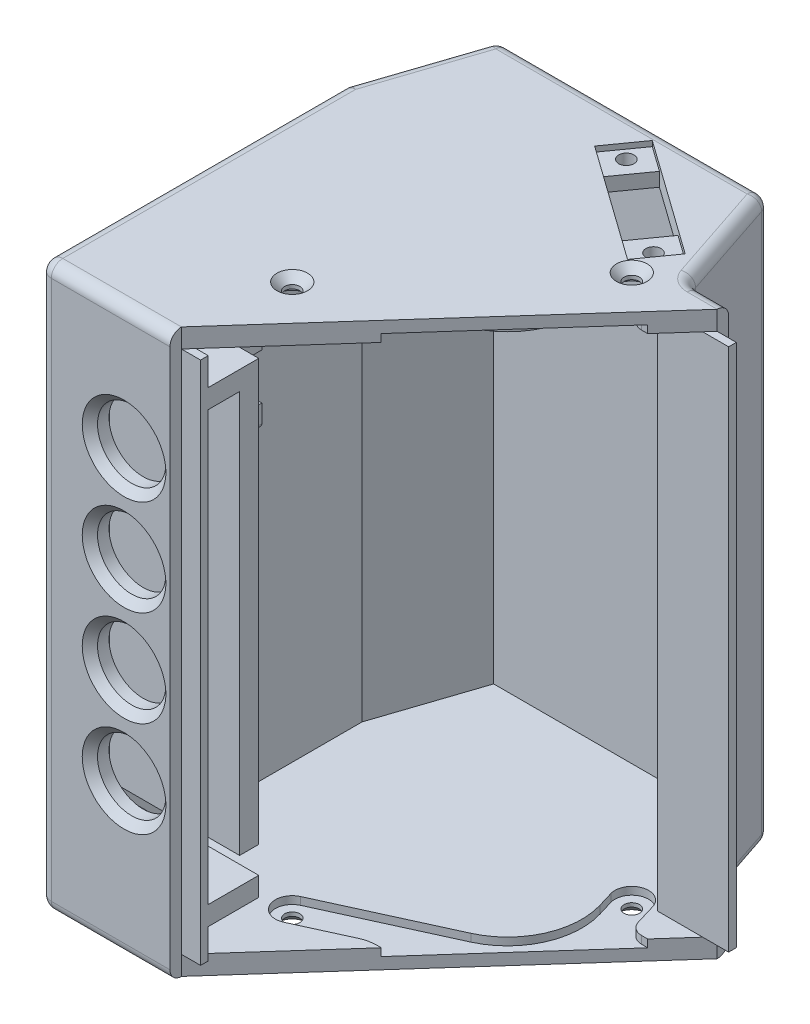
SolidWorks part; units mm, degrees
ref_plane "Plan de face" through (0, 0, 0) normal (0, 0, 1) x (1, 0, 0)
ref_plane "Plan de dessus" through (0, 0, 0) normal (0, 1, 0) x (1, 0, 0)
ref_plane "Plan de droite" through (0, 0, 0) normal (1, 0, 0) x (0, 0, -1)
sketch "Esquisse1" plane through (0, 0, 0) normal (0, 1, 0) x (1, 0, 0)
  line L0 (-33, 1.5) -> (-35.5, 1.5)
  line L1 (-35.5, 1.5) -> (-35.5, 0)
  line L2 (-35.5, 0) -> (-52.5, 0)
  line L3 (-52.5, 0) -> (-52.5, 40)
  line L4 (-52.5, 40) -> (-47.5, 55)
  line L5 (-47.5, 55) -> (-12.5, 55)
  line L6 (-12.5, 55) -> (-7.5, 40)
  line L7 (-7.5, 40) -> (-2.5, 40)
  line L8 (-2.5, 40) -> (-2.5, 38.5)
  line L9 (-2.5, 38.5) -> (0, 38.5)
  line L10 (0, 38.5) -> (0, 37.5)
  line L11 (0, 37.5) -> (-9.3019, 37.5)
  line L12 (-9.3019, 37.5) -> (-14.3019, 52.5)
  line L13 (-14.3019, 52.5) -> (-45.6981, 52.5)
  line L14 (-45.6981, 52.5) -> (-50, 39.5943)
  line L15 (-50, 39.5943) -> (-50, 2.5)
  line L16 (-50, 2.5) -> (-33, 2.5)
  line L17 (-33, 2.5) -> (-33, 1.5)
  dimension "D1" = 40
  dimension "D2" = 2.5
  dimension "D3" = 1.5
  dimension "D4" = 2.5
  dimension "D5" = 1
  dimension "D6" = 1.5
  dimension "D7" = 2.5
  dimension "D8" = 2.5
  dimension "D9" = 2.5
  dimension "D10" = 2.5
  dimension "D11" = 2.5
  dimension "D12" = 2.5
  dimension "D13" = 5
  dimension "D14" = 15
  dimension "D15" = 15
  dimension "D16" = 5
  dimension "D17" = 35
  dimension "D18" = 19.5
  dimension "D19" = 5
  dimension "D20" = 0
extrude "Boss.-Extru.1" add sketch "Esquisse1" along normal blind 68.5
sketch "Esquisse2" plane through (0, 0, 0) normal (0, -1, 0) x (1, 0, 0)
  line L0 (-35.5, 0) -> (-35.5, -1.5)
  line L1 (-35.5, -1.5) -> (-2.5, -38.5)
  line L2 (-2.5, -38.5) -> (-2.5, -40)
  line L3 (-2.5, -40) -> (-7.5, -40)
  line L4 (-7.5, -40) -> (-12.5, -55)
  line L5 (-12.5, -55) -> (-47.5, -55)
  line L6 (-47.5, -55) -> (-52.5, -40)
  line L7 (-52.5, -40) -> (-52.5, 0)
  line L8 (-52.5, 0) -> (-35.5, 0)
extrude "Boss.-Extru.2" add sketch "Esquisse2" along normal blind 2.5
sketch "Esquisse4" plane through (0, 0, 0) normal (0, 0, 1) x (1, 0, 0)
  line L0 (-33, 68.5) -> (-33, 0) construction
  line L1 (-52.5, 68.5) -> (-35.5, 68.5) construction
  circle A0 centre (-41.5, 55.01) radius 4.465
  circle A1 centre (-41.5, 42.47) radius 4.465
  circle A2 centre (-41.5, 29.93) radius 4.465
  circle A3 centre (-41.5, 17.39) radius 4.465
  dimension "D4" = 8.93
  dimension "D5" = 8.93
  dimension "D6" = 8.93
  dimension "D7" = 8.93
  dimension "D9" = 13.49
  dimension "D1" = 12.54
  dimension "D2" = 12.54
  dimension "D3" = 12.54
  dimension "D8" = 8.5
extrude "Enlèv. mat.-Extru.1" cut sketch "Esquisse4" against normal blind 2.5
chamfer "Chanfrein1" distance 1 angle 45 4 edges at (-37.035, 17.39, 0) (-37.035, 29.93, 0) (-37.035, 42.47, 0) (-37.035, 55.01, 0)
sketch "Esquisse6" plane through (-50, 0, 0) normal (1, 0, 0) x (0, 0, -1)
  line L0 (2.5, 64.89) -> (9.1, 64.89)
  line L9 (2.5, 68.5) -> (2.5, 0) construction
  line L10 (9.1, 64.89) -> (9.1, 9.89)
  line L11 (9.1, 3.89) -> (2.5, 3.89)
  line L12 (2.5, 3.89) -> (2.5, 6.39)
  line L13 (2.5, 68.5) -> (2.5, 0) construction
  line L15 (6.6, 9.89) -> (6.6, 62.39)
  line L16 (6.6, 62.39) -> (2.5, 62.39)
  line L17 (9.1, 6.39) -> (9.1, 3.89)
  line L18 (6.6, 9.89) -> (9.1, 9.89)
  line L22 (2.5, 6.39) -> (9.1, 6.39)
  line L27 (2.5, 62.39) -> (2.5, 64.89)
  dimension "D1" = 2.5
  dimension "D2" = 4.1
  dimension "D3" = 6.6
  dimension "D4" = 2.5
  dimension "D5" = 3.5
  dimension "D6" = 2.5
  dimension "D7" = 56
  dimension "D8" = 6.535
extrude "Boss.-Extru.3" add sketch "Esquisse6" along normal blind 17
sketch "Esquisse7" plane through (0, 68.5, 0) normal (0, 1, 0) x (1, 0, 0)
  line L0 (-35.5, 1.5) -> (-2.5, 38.5)
  line L1 (-2.5, 38.5) -> (-2.5, 40)
  line L2 (-2.5, 40) -> (-7.5, 40)
  line L3 (-7.5, 40) -> (-12.5, 55)
  line L4 (-12.5, 55) -> (-47.5, 55)
  line L5 (-47.5, 55) -> (-52.5, 40)
  line L6 (-52.5, 40) -> (-52.5, 0)
  line L7 (-52.5, 0) -> (-35.5, 0)
  line L8 (-35.5, 0) -> (-35.5, 1.5)
extrude "Boss.-Extru.4" add sketch "Esquisse7" along normal blind 2.5
fillet "Congé1" radius 1.5 17 edges at (-5, -2.5, -40) (-10, -2.5, -47.5) (-30, -2.5, -55) (-50, -2.5, -47.5) (-52.5, -2.5, -20) (-44, -2.5, 0) (-7.5, 34.25, -40) (-12.5, 34.25, -55) (-47.5, 34.25, -55) (-52.5, 34.25, -40) (-52.5, 34.25, 0) (-5, 71, -40) (-44, 71, 0) (-52.5, 71, -20) (-50, 71, -47.5) (-30, 71, -55) (-10, 71, -47.5)
sketch "Esquisse12" plane through (0, 0, 0) normal (0, 1, 0) x (1, 0, 0)
  circle A2 centre (-12.2172, 37.0607) radius 1
  circle A3 centre (-33.3477, 13.8264) radius 1
extrude "Enlèv. mat.-Extru.2" cut sketch "Esquisse12" against normal blind 2.5
chamfer "Chanfrein2" distance 1 angle 45 2 edges at (-33.3477, -2.5, -12.8264) (-12.2172, -2.5, -36.0607)
sketch "Esquisse13" plane through (0, 71, 0) normal (0, 1, 0) x (1, 0, 0)
  circle A0 centre (-12.2172, 37.0607) radius 1
  circle A1 centre (-33.3477, 13.8264) radius 1
extrude "Enlèv. mat.-Extru.3" cut sketch "Esquisse13" against normal blind 2.5
chamfer "Chanfrein3" distance 1 angle 45 2 edges at (-12.2172, 71, -36.0607) (-33.3477, 71, -12.8264)
sketch "Esquisse14" plane through (0, 0, 0) normal (0, 1, 0) x (1, 0, 0)
  line L18 (-6.5124, 33.7003) -> (-7.5707, 33.7003)
  line L19 (-22.9245, 15.2992) -> (-6.5124, 33.7003)
  line L20 (-22.9245, 15.2992) -> (-23.7683, 15.2992)
  line L21 (-32.4354, 11.8244) -> (-25.7587, 14.867)
  line L22 (-34.26, 15.8282) -> (-18.9837, 22.7898)
  line L23 (-14.3238, 36.4267) -> (-13.7173, 34.4105)
  line L24 (-10.1102, 37.6941) -> (-9.2944, 34.9819)
  line L25 (-35.5, 0) -> (-51, 0) construction
  line L26 (-52.5, 1.5) -> (-52.5, 39.7566) construction
  line L27 (76, 0) -> (-35.5, 0) construction
  arc A13 (-9.2944, 34.9819) -> (-7.5707, 33.7003) centre (-7.5707, 35.5003) ccw
  arc A14 (-23.7683, 15.2992) -> (-25.7587, 14.867) centre (-23.7683, 10.4992) ccw
  arc A15 (-34.26, 15.8282) -> (-32.4354, 11.8244) centre (-33.3477, 13.8263) ccw
  arc A16 (-18.9837, 22.7898) -> (-13.7173, 34.4105) centre (-23.0062, 31.6165) ccw
  arc A17 (-10.1102, 37.6941) -> (-14.3238, 36.4267) centre (-12.217, 37.0604) ccw
  dimension "D1" = 2.2
  dimension "D2" = 2.2
  dimension "D3" = 15.2992
  dimension "D4" = 4.8
  dimension "D5" = 3.0426
  dimension "D8" = 9.7
  dimension "D10" = 1.8
  dimension "D6" = 6.6766
  dimension "D7" = 114.5
  dimension "D9" = 2.8323
  dimension "D11" = 16.4121
  dimension "D12" = 18.4012
  dimension "D13" = 131.73
  dimension "D14" = 15.2763
  dimension "D15" = 6.9616
  dimension "D16" = 2.0162
  dimension "D17" = 0.6065
extrude "Enlèv. mat.-Extru.4" cut sketch "Esquisse14" against normal blind 1
sketch "Esquisse16" plane through (0, 68.5, 0) normal (0, -1, 0) x (1, 0, 0)
  line L0 (-34.26, -15.8284) -> (-18.9839, -22.7898)
  line L1 (-32.4353, -11.8244) -> (-25.7587, -14.867)
  line L2 (-9.2943, -34.9816) -> (-10.1108, -37.6946)
  line L3 (-23.1926, -15.2992) -> (-6.7808, -33.7003)
  line L4 (-7.5707, -33.7003) -> (-6.7808, -33.7003)
  line L7 (-14.3237, -36.4272) -> (-13.7171, -34.4103)
  line L8 (-23.7682, -15.2992) -> (-23.1926, -15.2992)
  line L11 (-9.3019, -37.5) -> (-3.3919, -37.5) construction
  arc A0 (-32.4353, -11.8244) -> (-34.26, -15.8284) centre (-33.3477, -13.8264) ccw
  arc A1 (-14.3237, -36.4272) -> (-10.1108, -37.6946) centre (-12.2172, -37.0607) ccw
  arc A2 (-13.7171, -34.4103) -> (-18.9839, -22.7898) centre (-23.0063, -31.6167) ccw
  arc A3 (-25.7587, -14.867) -> (-23.7682, -15.2992) centre (-23.7683, -10.4992) ccw
  arc A4 (-7.5707, -33.7003) -> (-9.2943, -34.9816) centre (-7.5707, -35.5003) ccw
  dimension "D1" = 4.4002
  dimension "D2" = 9.6
  dimension "D3" = 19.4004
  dimension "D4" = 4.3994
  dimension "D5" = 3.6
  dimension "D6" = 18.4012
  dimension "D7" = 16.4119
  dimension "D8" = 0.5756
  dimension "D9" = 0.7899
  dimension "D10" = 3.7997
extrude "Enlèv. mat.-Extru.5" cut sketch "Esquisse16" against normal blind 1
sketch "Esquisse17" plane through (-50, 0, 0) normal (1, 0, 0) x (0, 0, -1)
  line L0 (10.9, 62.09) -> (10.9, 55.99) construction
  line L1 (12.7, 62.09) -> (12.7, 55.99)
  line L2 (9.1, 62.09) -> (9.1, 55.99)
  line L3 (9.1, 9.89) -> (9.1, 64.89) construction
  line L4 (9.1, 64.89) -> (2.5, 64.89) construction
  arc A0 (12.7, 62.09) -> (9.1, 62.09) centre (10.9, 62.09) ccw
  arc A1 (9.1, 55.99) -> (12.7, 55.99) centre (10.9, 55.99) ccw
  point P2 (10.9, 59.04)
  dimension "D1" = 1.8
  dimension "D2" = 6.1
  dimension "D3" = 0
  dimension "D4" = 2.8
extrude "Enlèv. mat.-Extru.6" cut sketch "Esquisse17" against normal blind 2.5
chamfer "Chanfrein4" distance 0.5 angle 45 4 edges at (-52.5, 54.19, -10.9) (-52.5, 59.04, -9.1) (-52.5, 63.89, -10.9) (-52.5, 59.04, -12.7)
chamfer "Chanfrein5" distance 0.5 angle 45 3 edges at (-50, 54.19, -10.9) (-50, 59.04, -12.7) (-50, 63.89, -10.9)
sketch "Esquisse18" plane through (0, 0, -9.1) normal (0, 0, -1) x (-1, 0, 0)
  line L6 (50, 63.89) -> (37.6, 63.89)
  line L7 (37.6, 63.89) -> (37.6, 54.19)
  line L8 (37.6, 54.19) -> (50, 54.19)
  line L9 (50, 9.89) -> (50, 54.5582) construction
  line L10 (50, 54.19) -> (50, 53.19)
  line L11 (50, 53.19) -> (36.6, 53.19)
  line L12 (36.6, 53.19) -> (36.6, 64.89)
  line L13 (33, 64.89) -> (50, 64.89) construction
  line L14 (36.6, 64.89) -> (50, 64.89)
  line L15 (50, 64.89) -> (50, 63.89)
  line L16 (50, 64.39) -> (50, 62.09) construction
  line L18 (50, 62.09) -> (50, 55.99) construction
  dimension "D1" = 1
  dimension "D2" = 1
  dimension "D3" = 1
  dimension "D4" = 12.4
extrude "Boss.-Extru.5" add sketch "Esquisse18" along normal blind 4
fillet "Congé2" radius 0.5 2 edges at (-36.6, 53.19, -11.1) (-36.6, 64.89, -11.1)
sketch "Esquisse19" plane through (-36.6, 0, 0) normal (1, 0, 0) x (0, 0, -1)
  line L0 (13.1, 64.39) -> (13.1, 53.69) construction
  line L1 (13.1, 62.04) -> (11.1, 62.04)
  line L2 (13.1, 62.04) -> (13.1, 56.04)
  line L3 (13.1, 56.04) -> (11.1, 56.04)
  line L4 (11.1, 62.04) -> (11.1, 56.04)
  line L5 (9.1, 64.89) -> (13.1, 64.89) construction
  line L6 (13.1, 53.19) -> (9.1, 53.19) construction
  dimension "D1" = 6
  dimension "D2" = 2
  dimension "D3" = 2.85
  dimension "D4" = 2.85
extrude "Enlèv. mat.-Extru.7" cut sketch "Esquisse19" against normal blind 1
sketch "Esquisse20" plane through (0, 53.19, 0) normal (0, -1, 0) x (1, 0, 0)
  line L0 (-37.6, -9.1) -> (-37.6, -10.1)
  line L2 (-37.6, -10.1) -> (-41, -9.1)
  line L3 (-33, -9.1) -> (-50, -9.1) construction
  line L4 (-41, -9.1) -> (-37.6, -9.1)
  line L5 (-36.6, -9.1) -> (-36.6, -13.1) construction
  dimension "D1" = 1
  dimension "D2" = 1
  dimension "D3" = 3.4
extrude "Boss.-Extru.6" add sketch "Esquisse20" against normal up to vertex
sketch "Esquisse22" plane through (0, 71, 0) normal (0, 1, 0) x (1, 0, 0)
  line L0 (-22.5811, 51.0386) -> (-14.1138, 45)
  line L1 (-14.1138, 45) -> (-17.2492, 40.6035)
  line L2 (-17.2492, 40.6035) -> (-25.7166, 46.6421)
  line L3 (-25.7166, 46.6421) -> (-22.5811, 51.0386)
  line L8 (-9.2649, 40.5513) -> (-13.5811, 53.5) construction
  dimension "D1" = 10.4
  dimension "D2" = 5.4
  dimension "D3" = 36.07
  dimension "D4" = 8.5
  dimension "D5" = 9
extrude "Enlèv. mat.-Extru.8" cut sketch "Esquisse22" against normal blind 2.5
sketch "Esquisse23" plane through (0, 71, 0) normal (0, 1, 0) x (1, 0, 0)
  line L0 (-28.9732, 48.9646) -> (-13.9926, 38.281)
  line L5 (-13.9926, 38.281) -> (-10.8572, 42.6775)
  line L6 (-10.8572, 42.6775) -> (-25.8378, 53.3611)
  line L7 (-25.8378, 53.3611) -> (-28.9732, 48.9646)
  line L8 (-25.7166, 46.6421) -> (-17.2492, 40.6035) construction
  line L10 (-22.5811, 51.0386) -> (-25.7166, 46.6421) construction
  line L11 (-17.2492, 40.6035) -> (-14.1138, 45) construction
  line L12 (-14.1138, 45) -> (-22.5811, 51.0386) construction
  dimension "D1" = 4
  dimension "D2" = 4
extrude "Enlèv. mat.-Extru.9" cut sketch "Esquisse23" against normal blind 0.7
sketch "Esquisse24" plane through (0, 70.3, 0) normal (0, 1, 0) x (1, 0, 0)
  line L0 (-14.1138, 45) -> (-17.2492, 40.6035) construction
  line L1 (-25.7166, 46.6421) -> (-22.5811, 51.0386) construction
  line L2 (-26.1028, 50.2339) -> (-13.7275, 41.4082) construction
  line L3 (-10.8572, 42.6775) -> (-25.8378, 53.3611) construction
  circle A0 centre (-13.7275, 41.4082) radius 1
  circle A1 centre (-26.1028, 50.2339) radius 1
  dimension "D1" = 2
  dimension "D2" = 2
  dimension "D3" = 2.4
  dimension "D4" = 2.4
  dimension "D5" = 2.7
  dimension "D6" = 15.2
extrude "Enlèv. mat.-Extru.10" cut sketch "Esquisse24" against normal blind 1.8
